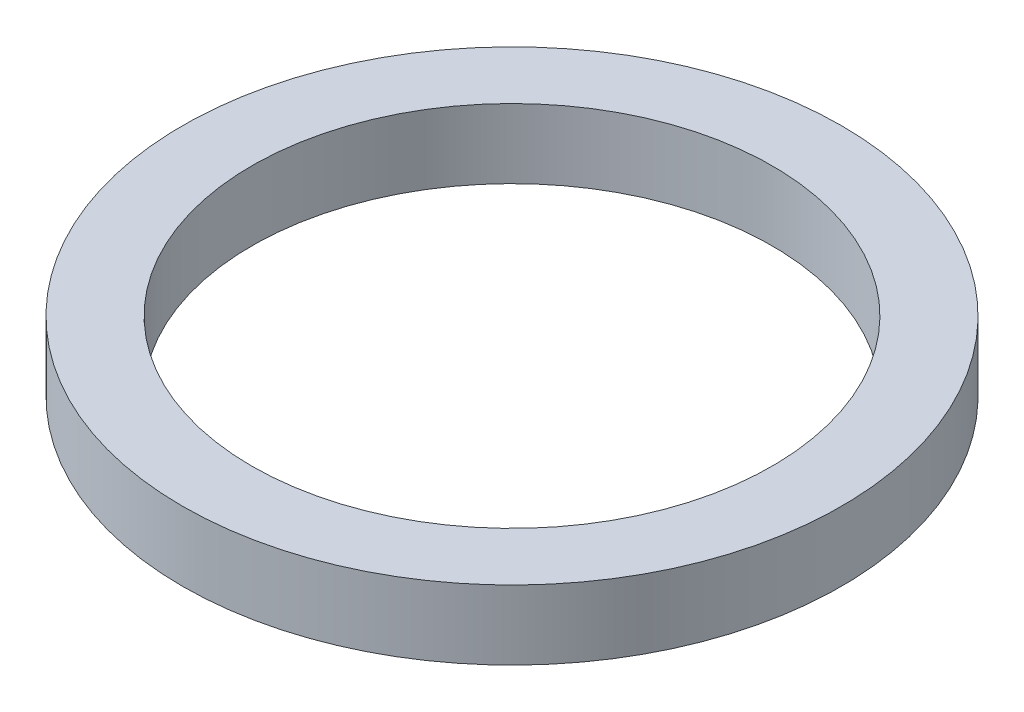
SolidWorks part; units mm, degrees
ref_plane "前视基准面" through (0, 0, 0) normal (0, 0, 1) x (1, 0, 0)
ref_plane "上视基准面" through (0, 0, 0) normal (0, 1, 0) x (1, 0, 0)
ref_plane "右视基准面" through (0, 0, 0) normal (1, 0, 0) x (0, 0, -1)
other "Configuration Table"
sketch "草图1" plane through (0, 0, 0) normal (0, 1, 0) x (1, 0, 0)
  circle A0 centre (0, 0) radius 37.5
  circle A1 centre (0, 0) radius 47.5
  dimension "D1" = 75
  dimension "D2" = 95
extrude "凸台-拉伸1" add sketch "草图1" along normal blind 10
